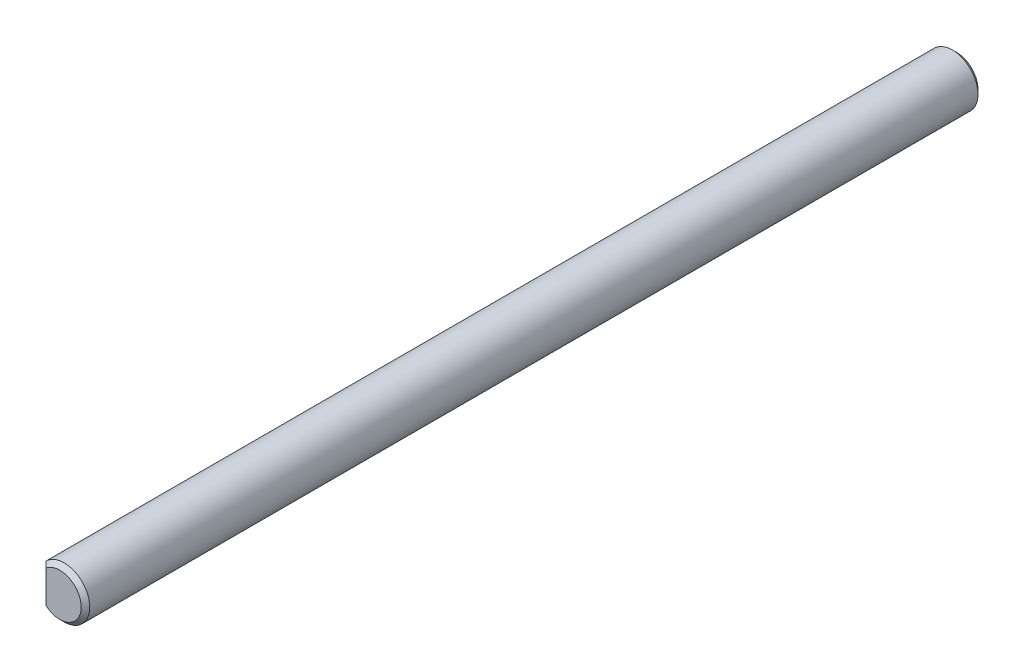
SolidWorks part; units mm, degrees
ref_plane "前视基准面" through (0, 0, 0) normal (0, 0, 1) x (1, 0, 0)
ref_plane "上视基准面" through (0, 0, 0) normal (0, 1, 0) x (1, 0, 0)
ref_plane "右视基准面" through (0, 0, 0) normal (1, 0, 0) x (0, 0, -1)
sketch "草图1" plane through (0, 0, 0) normal (0, 0, 1) x (1, 0, 0)
  circle A0 centre (0, 0) radius 3
  dimension "D1" = 6
extrude "凸台-拉伸1" add sketch "草图1" along normal blind 105
sketch "草图2" plane through (0, 0, 0) normal (0, 0, -1) x (-1, 0, 0)
  line L0 (-2.1213, 2.1213) -> (2.1213, 2.1213)
  line L1 (2.1213, 2.1213) -> (2.1213, -2.1213)
  line L2 (2.1213, -2.1213) -> (-2.1213, -2.1213)
  line L3 (-2.1213, -2.1213) -> (-2.1213, 2.1213)
  circle A0 centre (0, 0) radius 3 construction
  circle A1 centre (0, 0) radius 3
  circle M5 centre (0, 0) radius 3
extrude "切除-拉伸1" cut sketch "草图2" against normal blind 30 contours L1 M5
sketch "草图3" plane through (0, 0, 105) normal (0, 0, 1) x (1, 0, 0)
  line L0 (-2.1213, 2.1213) -> (2.1213, 2.1213)
  line L1 (2.1213, 2.1213) -> (2.1213, -2.1213)
  line L2 (2.1213, -2.1213) -> (-2.1213, -2.1213)
  line L3 (-2.1213, -2.1213) -> (-2.1213, 2.1213)
  circle A0 centre (0, 0) radius 3 construction
  circle A2 centre (0, 0) radius 3
  circle A3 centre (0, 0) radius 3
  circle M5 centre (0, 0) radius 3
  dimension "D1" = 0
extrude "切除-拉伸2" cut sketch "草图3" against normal blind 10 contours L3 M5
hole_wizard "M3x0.5 螺纹孔1" positions "草图4" profile "草图5" tap size "M3x0.5" standard "ANSI Metric"
sketch "草图4" plane through (0, 0, 0) normal (0, 0, -1) x (-1, 0, 0)
  point P0 (0, 0)
sketch "草图5" plane through (0, 0, 0) normal (1, 0, 0) x (0, 1, 0)
  line L0 (0, 0) -> (0, 10.7511)
  line L1 (0, 10.7511) -> (1.25, 10)
  line L2 (1.25, 10) -> (1.25, 0)
  line L5 (1.25, 0) -> (0, 0)
  line L10 (0, 10.7511) -> (-1.25, 10) construction
  line L11 (0, -6.35) -> (0, 107.95) construction
  dimension "螺纹孔钻头直径" = 2.5
  dimension "螺纹孔钻头深度" = 10
  dimension "导头角度" = 118
cosmetic thread "孔螺蚊线1" parameters "D1"=6, "D2"=3
chamfer "倒角1" distance 0.5 angle 45 4 edges at (-2.1213, 0, 0) (3, 0, 0) (3, 0, 105) (-2.1213, 0, 105)
